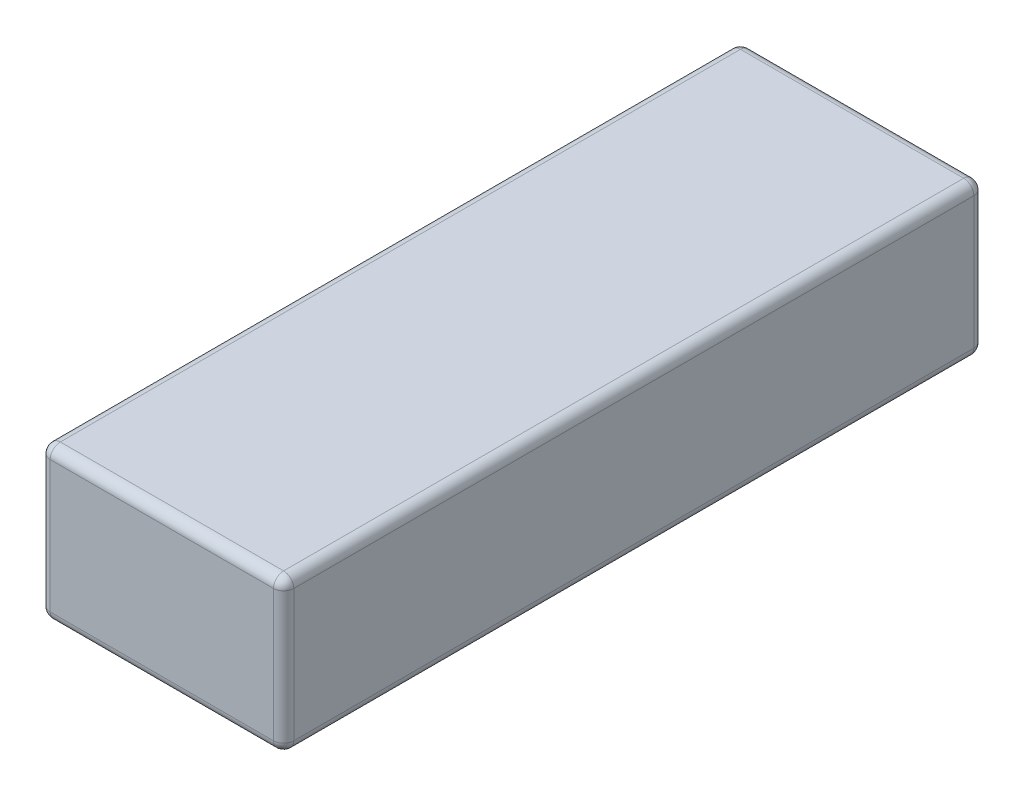
SolidWorks part; units mm, degrees
ref_plane "Спереди" through (0, 0, 0) normal (0, 0, 1) x (1, 0, 0)
ref_plane "Сверху" through (0, 0, 0) normal (0, 1, 0) x (1, 0, 0)
ref_plane "Справа" through (0, 0, 0) normal (1, 0, 0) x (0, 0, -1)
sketch "Эскиз1" plane through (0, 0, 0) normal (0, 0, 1) x (1, 0, 0)
  line L0 (0, 30) -> (0, 0)
  line L1 (0, 0) -> (48, 0)
  line L2 (48, 0) -> (48, 30)
  line L3 (48, 30) -> (0, 30)
  dimension "D1" = 30
  dimension "D2" = 48
extrude "Бобышка-Вытянуть1" add sketch "Эскиз1" against normal blind 138
fillet "Скругление1" radius 2 12 edges at (0, 30, -69) (24, 30, -138) (48, 30, -69) (24, 30, 0) (0, 15, -138) (48, 15, 0) (48, 15, -138) (0, 15, 0) (24, 0, -138) (24, 0, 0) (0, 0, -69) (48, 0, -69)
